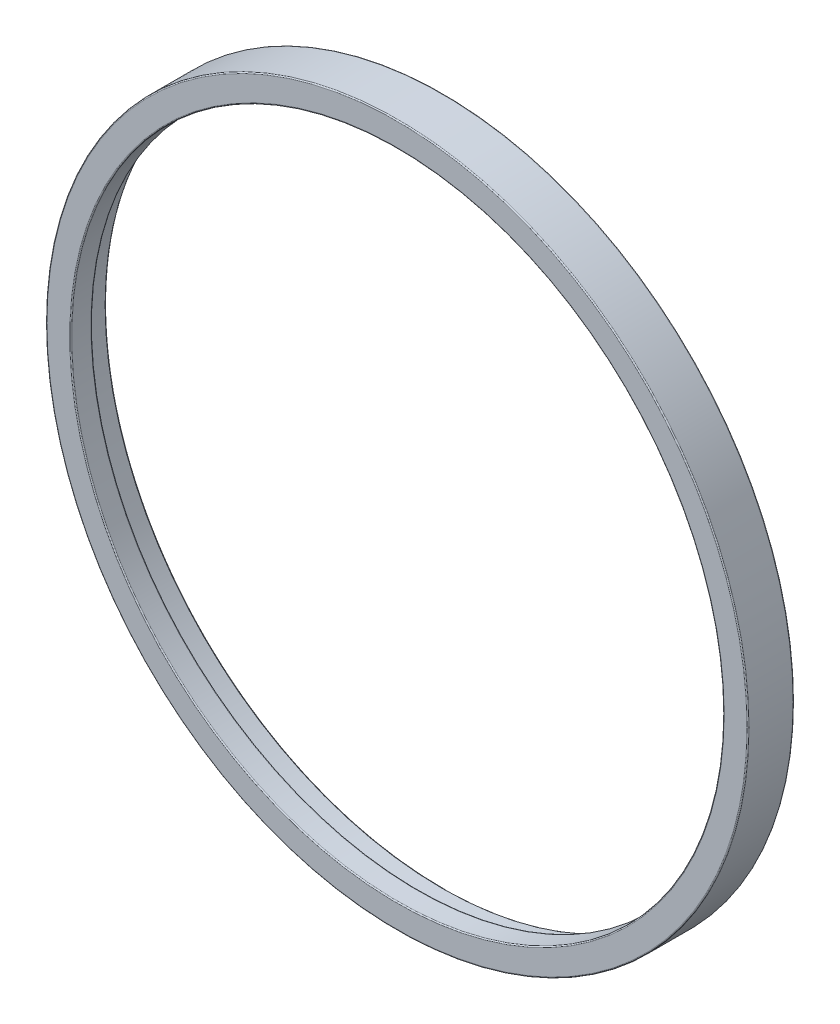
SolidWorks part; units mm, degrees
ref_plane "Front Plane" through (0, 0, 0) normal (0, 0, 1) x (1, 0, 0)
ref_plane "Top Plane" through (0, 0, 0) normal (0, 1, 0) x (1, 0, 0)
ref_plane "Right Plane" through (0, 0, 0) normal (1, 0, 0) x (0, 0, -1)
sketch "Sketch1" plane through (0, 0, 0) normal (1, 0, 0) x (0, 0, -1)
  line L0 (0, 46) -> (0, -48.4504) construction
  line L1 (-28.1792, 0) -> (23.724, 0) construction
  line L2 (0.15, 46) -> (2.85, 46)
  line L3 (3, 46.15) -> (3, 47.35)
  line L4 (3.15, 47.5) -> (6.35, 47.5)
  line L5 (6.5, 47.65) -> (6.5, 49.35)
  line L6 (6.35, 49.5) -> (0.15, 49.5)
  line L7 (0, 49.35) -> (0, 46.15)
  arc A0 (2.85, 46) -> (3, 46.15) centre (2.85, 46.15) ccw
  arc A1 (3, 47.35) -> (3.15, 47.5) centre (3.15, 47.35) cw
  arc A2 (6.35, 47.5) -> (6.5, 47.65) centre (6.35, 47.65) ccw
  arc A3 (6.5, 49.35) -> (6.35, 49.5) centre (6.35, 49.35) ccw
  arc A4 (0, 46.15) -> (0.15, 46) centre (0.15, 46.15) ccw
  arc A5 (0.15, 49.5) -> (0, 49.35) centre (0.15, 49.35) ccw
  point P5 (3, 47.6427)
  point P13 (3, 46)
  point P18 (6.5, 47.5)
  point P21 (6.5, 49.5)
  point P27 (0, 49.5)
  dimension "D6" = 0.15
  dimension "D1" = 46
  dimension "D2" = 3
  dimension "D3" = 3.5
  dimension "D4" = 2
  dimension "D5" = 6.5
revolve "Revolve1" add sketch "Sketch1" angle 360 about L1
